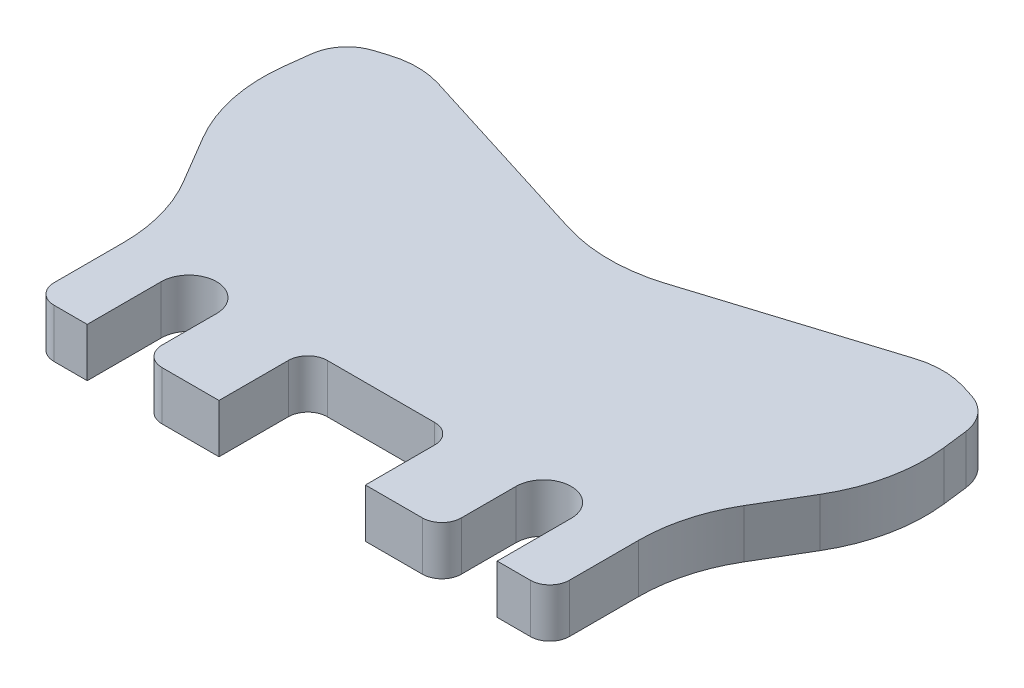
SolidWorks part; units mm, degrees
ref_plane "Front Plane" through (0, 0, 0) normal (0, 0, 1) x (1, 0, 0)
ref_plane "Top Plane" through (0, 0, 0) normal (0, 1, 0) x (1, 0, 0)
ref_plane "Right Plane" through (0, 0, 0) normal (1, 0, 0) x (0, 0, -1)
sketch "Sketch1" plane through (0, 0, 0) normal (0, 1, 0) x (1, 0, 0)
  line L0 (-4.5, 0) -> (4.5, 0)
  line L1 (4.5, 0) -> (4.5, -5.46)
  line L2 (4.5, -5.46) -> (9.2, -5.46)
  line L3 (9.2, -5.46) -> (9.2, -0.91)
  line L4 (12.6, -0.91) -> (12.6, -5.46)
  line L5 (12.6, -5.46) -> (15.84, -5.46)
  line L6 (15.84, -5.46) -> (15.84, 2.73)
  line L7 (15.84, 2.73) -> (20.705, 10.95)
  line L8 (20.705, 10.95) -> (19.91, 17.44)
  line L9 (19.91, 17.44) -> (16.145, 18.62)
  line L10 (16.145, 18.62) -> (0, 13.56)
  line L11 (0, -55) -> (0, 55) construction
  line L12 (-16.145, 18.62) -> (0, 13.56)
  line L13 (-19.91, 17.44) -> (-16.145, 18.62)
  line L14 (-20.705, 10.95) -> (-19.91, 17.44)
  line L15 (-15.84, 2.73) -> (-20.705, 10.95)
  line L16 (-15.84, -5.46) -> (-15.84, 2.73)
  line L17 (-12.6, -5.46) -> (-15.84, -5.46)
  line L18 (-12.6, -0.91) -> (-12.6, -5.46)
  line L19 (-9.2, -5.46) -> (-9.2, -0.91)
  line L20 (-4.5, -5.46) -> (-9.2, -5.46)
  line L21 (-4.5, 0) -> (-4.5, -5.46)
  arc A0 (9.2, -0.91) -> (12.6, -0.91) centre (10.9, -0.91) cw
  arc A1 (-9.2, -0.91) -> (-12.6, -0.91) centre (-10.9, -0.91) ccw
  point P17 (10.9, 0.79)
  point P32 (0, 0)
  dimension "D6" = 1.7
  dimension "D1" = 13.56
  dimension "D2" = 4.5
  dimension "D3" = 5.46
  dimension "D4" = 6.25
  dimension "D5" = 9.2
  dimension "D7" = 11.34
  dimension "D8" = 8.19
  dimension "D9" = 20.705
  dimension "D10" = 16.41
  dimension "D11" = 24.08
  dimension "D12" = 19.91
  dimension "D13" = 22.9
  dimension "D14" = 16.145
extrude "Boss-Extrude1" add sketch "Sketch1" along normal blind 3
fillet "Fillet1" radius 1.2 6 edges at (-15.84, 1.5, 5.46) (-9.2, 1.5, 5.46) (15.84, 1.5, 5.46) (9.2, 1.5, 5.46) (-4.5, 1.5, 0) (4.5, 1.5, 0)
fillet "Fillet2" radius 5 2 edges at (-16.145, 1.5, -18.62) (16.145, 1.5, -18.62)
fillet "Fillet3" radius 10 5 edges at (0, 1.5, -13.56) (15.84, 1.5, -2.73) (-15.84, 1.5, -2.73) (-20.705, 1.5, -10.95) (20.705, 1.5, -10.95)
fillet "Fillet4" radius 2.5 2 edges at (-19.91, 1.5, -17.44) (19.91, 1.5, -17.44)
